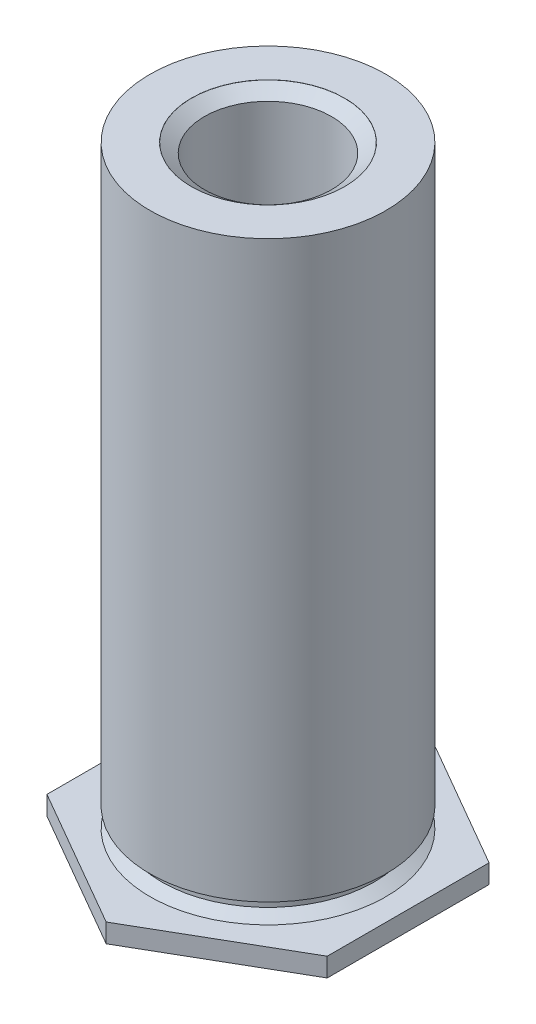
SolidWorks part; units mm, degrees
revolve "Body" add sketch "BodySke"
sketch "BodySke" plane through (0, 0, 0) normal (0, 0, 1) x (1, 0, 0)
  line L0 (2.695, 0) -> (3.712, 0)
  line L1 (3.712, 0) -> (3.712, 0.4312)
  line L2 (3.712, 0.4312) -> (2.695, 0.4312)
  line L3 (1.45, 14) -> (1.45, 7)
  line L4 (2.695, 0.884) -> (2.4255, 0.884)
  line L5 (2.4255, 0.884) -> (2.4255, 0.5868)
  line L6 (2.695, 0.0025) -> (2.695, 0)
  line L7 (1.016, 13.4) -> (3.6522, 13.4) construction
  line L8 (2.695, 14) -> (1.45, 14)
  line L9 (0, 0) -> (0, 15.24) construction
  line L10 (2.695, 0.0025) -> (0, 0.0025)
  line L11 (2.695, 14) -> (2.695, 0.884)
  line L12 (0, 7) -> (1.45, 7)
  line L13 (0, 7) -> (0, 0.0025)
  line L14 (1.016, 7) -> (3.6522, 7) construction
  line L15 (1.016, 13.9975) -> (3.6522, 13.9975) construction
  line L16 (2.695, 0.4312) -> (2.4255, 0.5868)
  dimension "D1" = 0.0025
  dimension "E_dia" = 7.424
  dimension "D2" = 30
  dimension "C_dia" = 5.39
  dimension "Thread_min" = 2.9
  dimension "Clinching_ht" = 0.4312
  dimension "Advance" = 0.6
  dimension "Length" = 14
  dimension "Thread_limit" = 7
  dimension "Thread_depth" = 7
  dimension "Drill_depth" = 0.0025
  dimension "Groove_wid" = 0.4528
  dimension "Groove_dia" = 4.851
cosmetic thread "ThreadCosmetic" [suppressed]
revolve "EndChamfer" cut sketch "EndChamferSke" angle 360 about L0
sketch "EndChamferSke" plane through (0, 0, 0) normal (0, 0, 1) x (1, 0, 0)
  line L0 (0, -2.54) -> (0, 7.62) construction
  line L1 (0, 0) -> (0, 15.24) construction
  line L2 (1.7515, 13.9975) -> (1.7515, 14.254)
  line L4 (1.7515, 13.9975) -> (1.75, 13.9975)
  line L6 (1.75, 13.9975) -> (1.45, 13.7875)
  line L8 (1.45, 13.7875) -> (1.45, 14.254)
  line L9 (1.7515, 14.254) -> (1.45, 14.254)
  line L10 (2.695, 14) -> (-2.695, 14) construction
  dimension "Inset" = 0.0025
  dimension "D1" = 0.254
  dimension "D2" = 34.99
  dimension "Thread_nominal" = 3.5
  dimension "Thread_min" = 2.9
revolve "TapDrill" cut sketch "TapDriSke" angle 360 about L0
sketch "TapDriSke" plane through (0, 0, 0) normal (0, 0, 1) x (1, 0, 0)
  line L0 (0, 0) -> (0, 15.24) construction
  line L1 (0, 0) -> (0, 15.24) construction
  line L2 (1.45, 4) -> (1.45, 14)
  line L3 (2.695, 14) -> (-2.695, 14) construction
  line L4 (1.45, 4) -> (0, 3.3994)
  line L5 (0, 3.3994) -> (0, 14)
  line L6 (0, 14) -> (1.45, 14)
  line L7 (1.45, 7) -> (1.45, 14) construction
  line L8 (0, 3.3994) -> (-1.45, 4) construction
  line L9 (-1.45, 14) -> (-1.45, 7) construction
  dimension "D1" = 135
  dimension "Depth" = 10
ref_plane "Plane1" through (0, 0, 0) normal (0, 0, 1) x (1, 0, 0)
ref_plane "Plane2" through (0, 0, 0) normal (0, 1, 0) x (1, 0, 0)
ref_plane "Plane3" through (0, 0, 0) normal (1, 0, 0) x (0, 0, -1)
ref_plane "Plane4" through (0, -0.5486, 0) normal (0, 1, 0) x (-1, 0, 0)
sketch "ThdSchSke" plane through (0, 0, 0) normal (0, 0, 1) x (1, 0, 0)
  line L0 (0, -5.08) -> (0, 7.62) construction
  line L1 (0, 0) -> (0, 15.24) construction
  line L2 (0, 13.9975) -> (1.75, 13.9975) construction
  line L4 (1.75, 13.9975) -> (1.45, 14.2075)
  line L5 (1.7515, 13.9975) -> (-1.7515, 13.9975) construction
  line L6 (1.75, 13.9975) -> (1.45, 13.7874)
  line L7 (1.45, 14.2075) -> (1.45, 13.7874)
  dimension "Thread_nominal" = 3.5
  dimension "Thread_min" = 2.9
revolve "ThreadSchematic" [suppressed] cut sketch "ThdSchSke" angle 360 about L0
pattern_linear "ThdSchPat" [suppressed]
sketch "HexDieSke" plane through (0, 0.4312, 0) normal (0, 1, 0) x (-1, 0, 0)
  line L0 (0, 3.695) -> (3.2, 1.8475)
  line L1 (3.2, 1.8475) -> (3.2, -1.8475)
  line L2 (3.2, -1.8475) -> (0, -3.695)
  line L3 (0, -3.695) -> (-3.2, -1.8475)
  line L4 (-3.2, -1.8475) -> (-3.2, 1.8475)
  line L5 (-3.2, 1.8475) -> (0, 3.695)
  circle A1 centre (0, 0) radius 3.2 construction
  circle A2 centre (0, 0) radius 3.695 construction
  circle A3 centre (0, 0) radius 3.7125
extrude "HexDie" cut sketch "HexDieSke" against normal blind 0.4312
equation "' \"Length@BodySke\" = 14"
equation "' \"C_dia@BodySke\" = 5.39"
equation "' \"Thread_depth@BodySke\" = 7 'always explicit"
equation "' \"Drill_depth@BodySke\" = 0.001 'implicit, or explicit"
equation "' \"Width_across_flats@HexDieSke\" = 6.4"
equation "' \"Advance@BodySke\" = 0.6"
equation "' \"Thread_min@BodySke\" = 2.9"
equation "' \"Thread_nominal@ThreadCosmetic\" = 3.5"
equation "\"B_dia@EndChamferSke\" = \"Thread_nominal@ThreadCosmetic\" + 0.003"
equation "\"E_dia@BodySke\" = \"Width_across_flats@HexDieSke\" * 1.16"
equation "\"Clinching_ht@BodySke\" = \"C_dia@BodySke\" * 0.08"
equation "\"Groove_dia@BodySke\" = \"C_dia@BodySke\" * 0.9"
equation "\"Groove_wid@BodySke\" = \"Clinching_ht@BodySke\" * 1.05"
equation "\"Thread_limit@BodySke\" = ((sgn( \"Length@BodySke\" - 0.006 - \"Thread_depth@BodySke\" )-1)*( \"Length@BodySke\" - 0.006 - \"Thread_depth@BodySke\" ))/-2+ \"Thread_depth@BodySke\""
equation "\"Depth@TapDriSke\" = \"Thread_limit@BodySke\" + \"Advance@BodySke\" * 5"
equation "\"Depth@TapDriSke\" = ((sgn( \"Depth@TapDriSke\" - \"Drill_depth@BodySke\" )+1)*( \"Depth@TapDriSke\" - \"Drill_depth@BodySke\" ))/2 +\"Drill_depth@BodySke\""
equation "\"Depth@HexDie\" = \"Clinching_ht@BodySke\""
equation "\"OD@HexDieSke\" =  \"Width_across_flats@HexDieSke\" * 1.16 + 0.001"
equation "\"Thread_nominal@EndChamferSke\" = \"Thread_nominal@ThreadCosmetic\""
equation "\"Thread_min@EndChamferSke\" = \"Thread_min@BodySke\""
equation "\"D2@EndChamferSke\" = \"Vee_angle@ThdSchSke\" / 2 - 0.01"
equation "\"Thread_nominal@ThdSchSke\" = \"Thread_nominal@ThreadCosmetic\""
equation "\"Thread_min@ThdSchSke\" = \"Thread_min@BodySke\""
equation "\"Num_threads@ThdSchPat\" = int(  ( \"Thread_limit@BodySke\" - \"Inset@EndChamferSke\" ) / \"Advance@BodySke\" + 0.999 )  + 1"
equation "\"Advance@ThdSchPat\" = (  \"Thread_limit@BodySke\" - \"Inset@EndChamferSke\" ) /  (\"Num_threads@ThdSchPat\" - 1) 'relax it"
